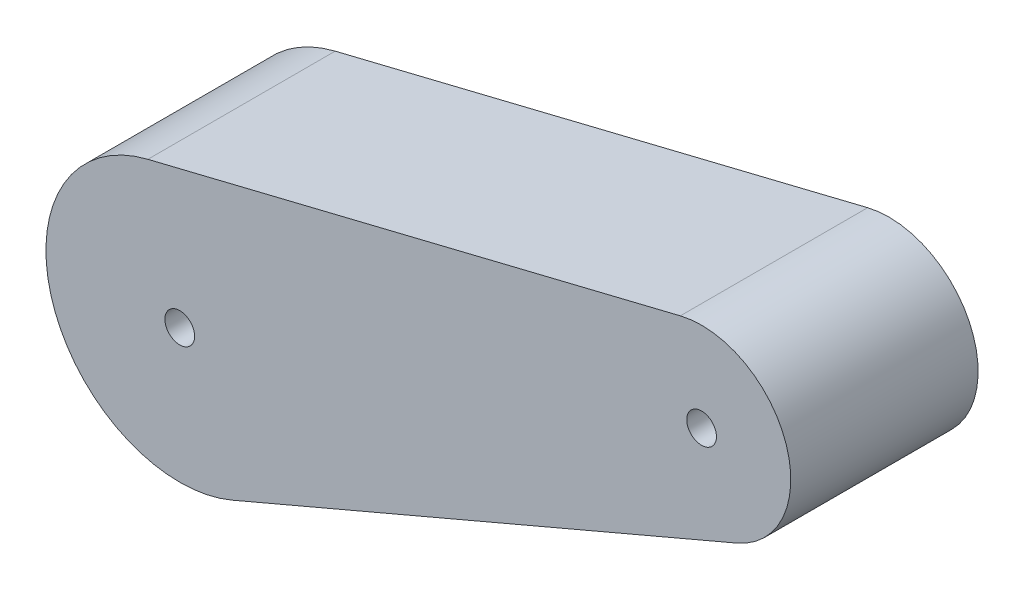
SolidWorks part; units mm, degrees
ref_plane "前基準面" through (0, 0, 0) normal (0, 0, 1) x (1, 0, 0)
ref_plane "上基準面" through (0, 0, 0) normal (0, 1, 0) x (1, 0, 0)
ref_plane "右基準面" through (0, 0, 0) normal (1, 0, 0) x (0, 0, -1)
sketch "草圖1" plane through (0, 0, 0) normal (0, 0, 1) x (1, 0, 0)
  line L0 (-10.7241, 43.7035) -> (168.3543, 87.6461)
  line L1 (17.6468, -41.3955) -> (187.2681, 30.9134)
  line L2 (0, 0) -> (175.5036, 58.5105) construction
  arc A0 (-10.7241, 43.7035) -> (17.6468, -41.3955) centre (0, 0) ccw
  arc A1 (187.2681, 30.9134) -> (168.3543, 87.6461) centre (175.5036, 58.5105) ccw
  circle A2 centre (175.5036, 58.5105) radius 5
  circle A3 centre (0, 0) radius 5
  dimension "D1" = 90
  dimension "D3" = 60
  dimension "D2" = 185
extrude "Boss-Extrude1" add sketch "草圖1" along normal mid plane 63
sketch "Sketch1" plane through (0, 0, -31.5) normal (0, 0, -1) x (-1, 0, 0)
  circle A0 centre (-175.5036, 58.5105) radius 5
